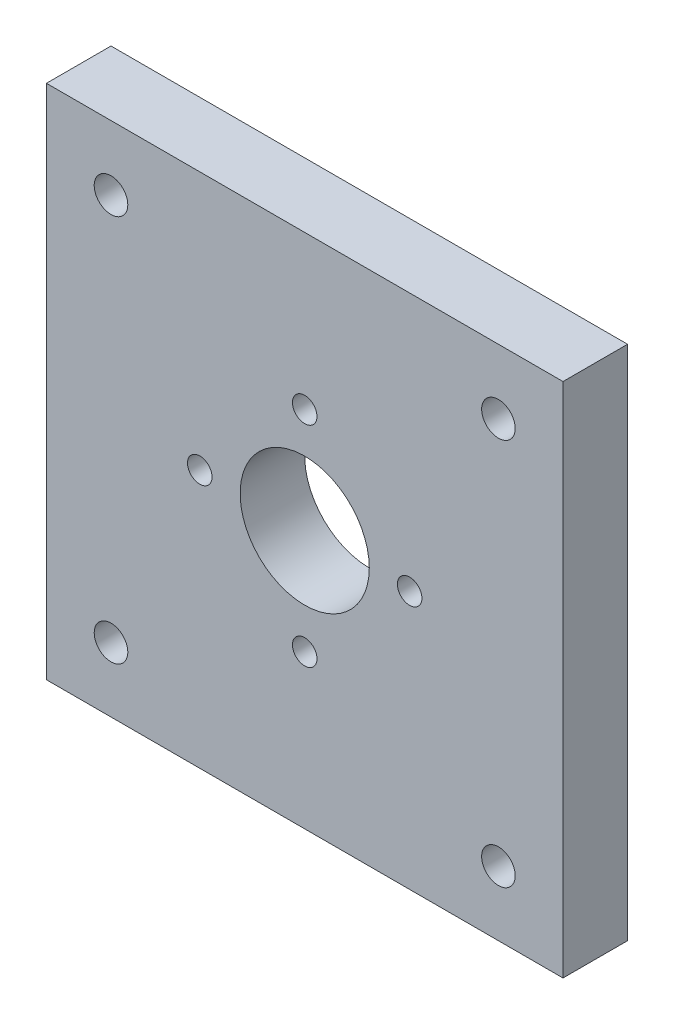
SolidWorks part; units mm, degrees
ref_plane "Front Plane" through (0, 0, 0) normal (0, 0, 1) x (1, 0, 0)
ref_plane "Top Plane" through (0, 0, 0) normal (0, 1, 0) x (1, 0, 0)
ref_plane "Right Plane" through (0, 0, 0) normal (1, 0, 0) x (0, 0, -1)
sketch "Sketch1" plane through (0, 0, 0) normal (0, 0, 1) x (1, 0, 0)
  line L0 (0, 4) -> (4, 0) construction
  line L1 (0, 0) -> (4, 0)
  line L2 (0, 0) -> (0, 4)
  line L3 (0, 4) -> (4, 4)
  line L4 (4, 0) -> (4, 4)
  line L5 (0, 0) -> (4, 4) construction
  line L6 (0, 2) -> (4, 2) construction
  circle A0 centre (2, 2) radius 0.5
  circle A1 centre (2, 2) radius 0.8125 construction
  circle A2 centre (2, 2.8125) radius 0.095
  circle A3 centre (0.5, 3.5) radius 0.13
  circle A4 centre (3.5, 3.5) radius 0.13
  circle A5 centre (2.8125, 2) radius 0.095
  circle A6 centre (2, 1.1875) radius 0.095
  circle A7 centre (1.1875, 2) radius 0.095
  circle A8 centre (3.5, 0.5) radius 0.13
  circle A9 centre (0.5, 0.5) radius 0.13
  point P25 (2, 2)
  dimension "D3" = 1
  dimension "D4" = 1.625
  dimension "D5" = 0.19
  dimension "D6" = 0.26
  dimension "D7" = 0.26
  dimension "D1" = 4
  dimension "D2" = 4
  dimension "D8" = 1.5
  dimension "D9" = 1.5
  dimension "D10" = 4
extrude "Boss-Extrude1" add sketch "Sketch1" along normal blind 0.5
